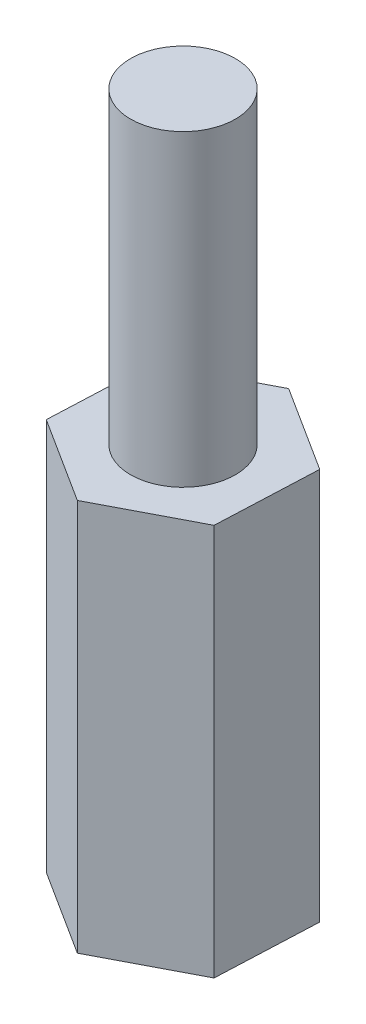
SolidWorks part; units mm, degrees
ref_plane "Front Plane" through (0, 0, 0) normal (0, 0, 1) x (1, 0, 0)
ref_plane "Top Plane" through (0, 0, 0) normal (0, 1, 0) x (1, 0, 0)
ref_plane "Right Plane" through (0, 0, 0) normal (1, 0, 0) x (0, 0, -1)
sketch "Sketch1" plane through (0, 0, 0) normal (0, 1, 0) x (1, 0, 0)
  line L1 (3.2104, 1.6725) -> (0.1568, 3.6166)
  line L2 (0.1568, 3.6166) -> (-3.0537, 1.9441)
  line L3 (-3.0537, 1.9441) -> (-3.2104, -1.6725)
  line L4 (-3.2104, -1.6725) -> (-0.1568, -3.6166)
  line L5 (-0.1568, -3.6166) -> (3.0537, -1.9441)
  line L6 (3.0537, -1.9441) -> (3.2104, 1.6725)
  circle A0 centre (0, 0) radius 3.135 construction
  dimension "D1" = 6.27
extrude "Boss-Extrude1" add sketch "Sketch1" along normal blind 25
sketch "Sketch2" plane through (0, 25, 0) normal (0, 1, 0) x (1, 0, 0)
  circle A0 centre (0, 0) radius 1.8731
extrude "Cut-Extrude1" cut sketch "Sketch2" against normal blind 11 flip side to cut
